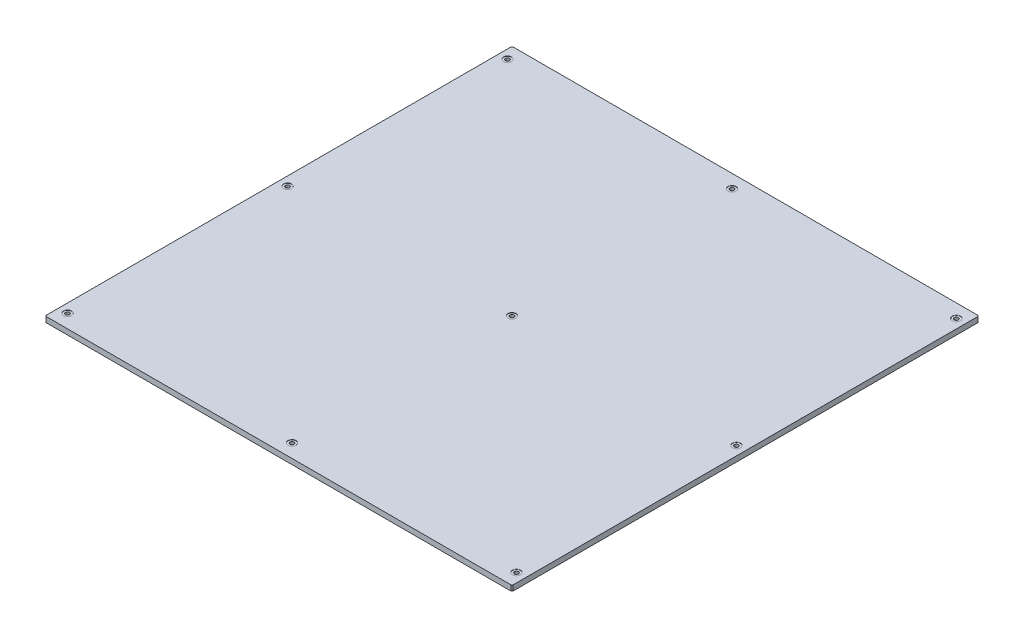
SolidWorks part; units mm, degrees
ref_plane "前视基准面" through (0, 0, 0) normal (0, 0, 1) x (1, 0, 0)
ref_plane "上视基准面" through (0, 0, 0) normal (0, 1, 0) x (1, 0, 0)
ref_plane "右视基准面" through (0, 0, 0) normal (1, 0, 0) x (0, 0, -1)
other "Configuration Table"
sketch "草图1" plane through (0, 0, 0) normal (0, 1, 0) x (1, 0, 0)
  line L1 (-520, 520) -> (520, 520)
  line L2 (-520, 520) -> (-520, -520)
  line L3 (-520, -520) -> (520, -520)
  line L4 (520, 520) -> (520, -520)
  line L5 (-520, 520) -> (520, -520) construction
  line L6 (-520, -520) -> (520, 520) construction
  point P0 (0, 0)
  dimension "D1" = 1040
  dimension "D2" = 1040
extrude "凸台-拉伸1" add sketch "草图1" along normal blind 12
chamfer "倒角1" distance 2 angle 45 4 edges at (520, 6, -520) (-520, 6, -520) (-520, 6, 520) (520, 6, 520)
hole_wizard "M8 六角头螺栓的柱形沉头孔1" positions "草图2" profile "草图3" counterbore size "M8" standard "GB" end condition through all
sketch "草图2" plane through (77.5245, 12, 0) normal (0, 1, 0) x (1, 0, 0)
  point P0 (-577.5245, 490)
  point P3 (-77.5245, 490)
  point P6 (422.4755, 490)
  point P9 (-577.5245, 0)
  point P12 (-77.5245, 0)
  point P15 (422.4755, 0)
  point P18 (-577.5245, -490)
  point P21 (-77.5245, -490)
  point P24 (422.4755, -490)
sketch "草图3" plane through (-500, 12, -490) normal (1, 0, 0) x (0, 0, 1)
  line L0 (0, 0) -> (0, 12)
  line L1 (0, 12) -> (4.5, 12)
  line L2 (4.5, 12) -> (4.5, 0.5)
  line L3 (9, 0.5) -> (4.5, 0.5)
  line L4 (9, 0.5) -> (9, 0.025)
  line L5 (9, 0.025) -> (9.025, 0)
  line L6 (9.025, 0) -> (0, 0)
  line L7 (-9, 0.025) -> (-9.025, 0) construction
  line L8 (0, -6.35) -> (0, 107.95) construction
  dimension "通孔孔直径" = 9
  dimension "通孔孔深度" = 12
  dimension "柱形沉头孔直径" = 18
  dimension "柱形沉头孔深度" = 0.5
  dimension "近端锥形沉头孔直径" = 18.05
  dimension "近端锥形沉头孔角度" = 90
